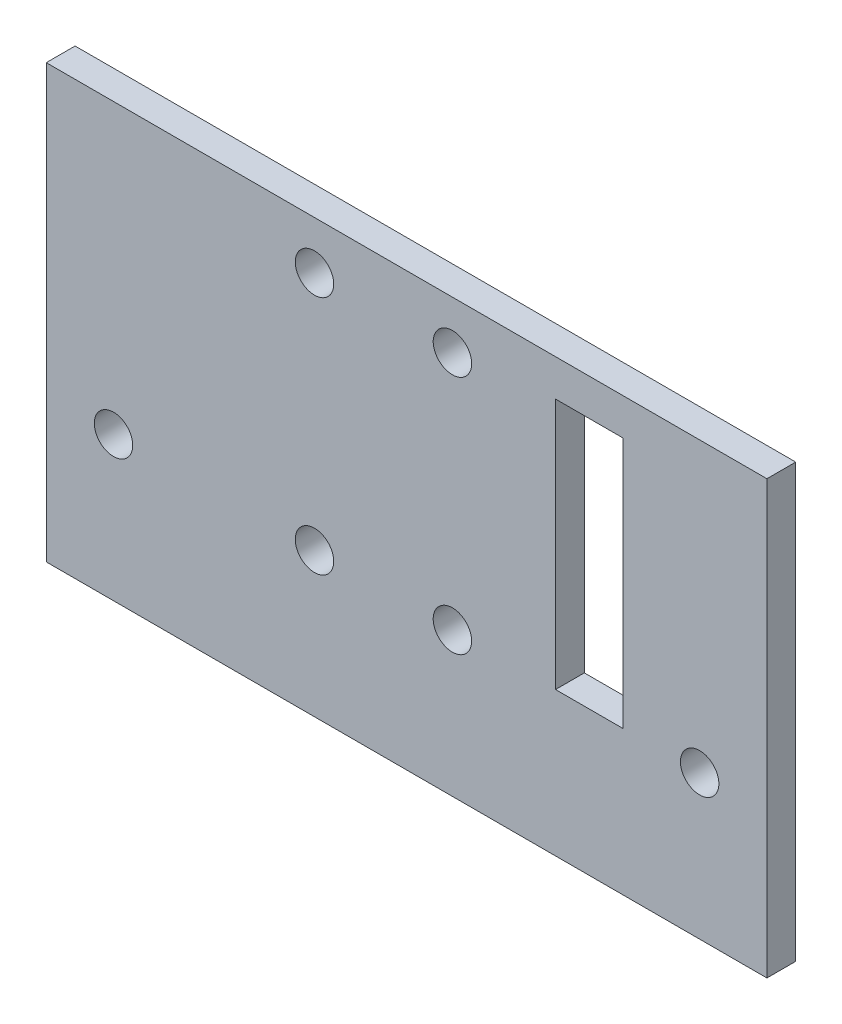
SolidWorks part; units mm, degrees
ref_plane "Front Plane" through (0, 0, 0) normal (0, 0, 1) x (1, 0, 0)
ref_plane "Top Plane" through (0, 0, 0) normal (0, 1, 0) x (1, 0, 0)
ref_plane "Right Plane" through (0, 0, 0) normal (1, 0, 0) x (0, 0, -1)
sketch "Sketch1" plane through (0, 0, 0) normal (0, 0, 1) x (1, 0, 0)
  line L1 (-37.5, -20) -> (37.5, -20)
  line L2 (-37.5, -20) -> (-37.5, 20)
  line L3 (-37.5, 20) -> (37.5, 20)
  line L4 (37.5, -20) -> (37.5, 20)
  line L5 (-37.5, -20) -> (37.5, 20) construction
  line L6 (-37.5, 20) -> (37.5, -20) construction
  line L7 (15.5, 16.182) -> (22.5, 16.182)
  line L8 (15.5, 16.182) -> (15.5, -10)
  line L9 (15.5, -10) -> (22.5, -10)
  line L10 (22.5, 16.182) -> (22.5, -10)
  circle A0 centre (-30.5, -10) radius 2
  circle A1 centre (30.5, -10) radius 2
  circle A2 centre (4.771, 15) radius 2
  circle A3 centre (4.771, -10) radius 2
  circle A4 centre (-9.5838, -10) radius 2
  circle A5 centre (-9.5838, 15) radius 2
  point P0 (0, 0)
  dimension "D2" = 4
  dimension "D3" = 4
  dimension "D12" = 25
  dimension "D15" = 4
  dimension "D16" = 4
  dimension "D17" = 4
  dimension "D18" = 4
  dimension "D1" = 75
  dimension "D4" = 10
  dimension "D5" = 7
  dimension "D6" = 7
  dimension "D7" = 7
  dimension "D8" = 15
  dimension "D9" = 40
  dimension "D10" = 10
  dimension "D11" = 10
  dimension "D13" = 25
  dimension "D14" = 10
extrude "Boss-Extrude1" add sketch "Sketch1" along normal blind 3
sketch "Sketch2" plane through (0, 0, 0) normal (0, 0, 1) x (1, 0, 0)
  line L1 (-37.5, -20) -> (37.5, -20)
  line L2 (-37.5, -20) -> (-37.5, -25)
  line L3 (-37.5, -25) -> (37.5, -25)
  line L4 (37.5, -20) -> (37.5, -25)
  dimension "D1" = 5
extrude "Boss-Extrude2" add sketch "Sketch2" along normal blind 3
